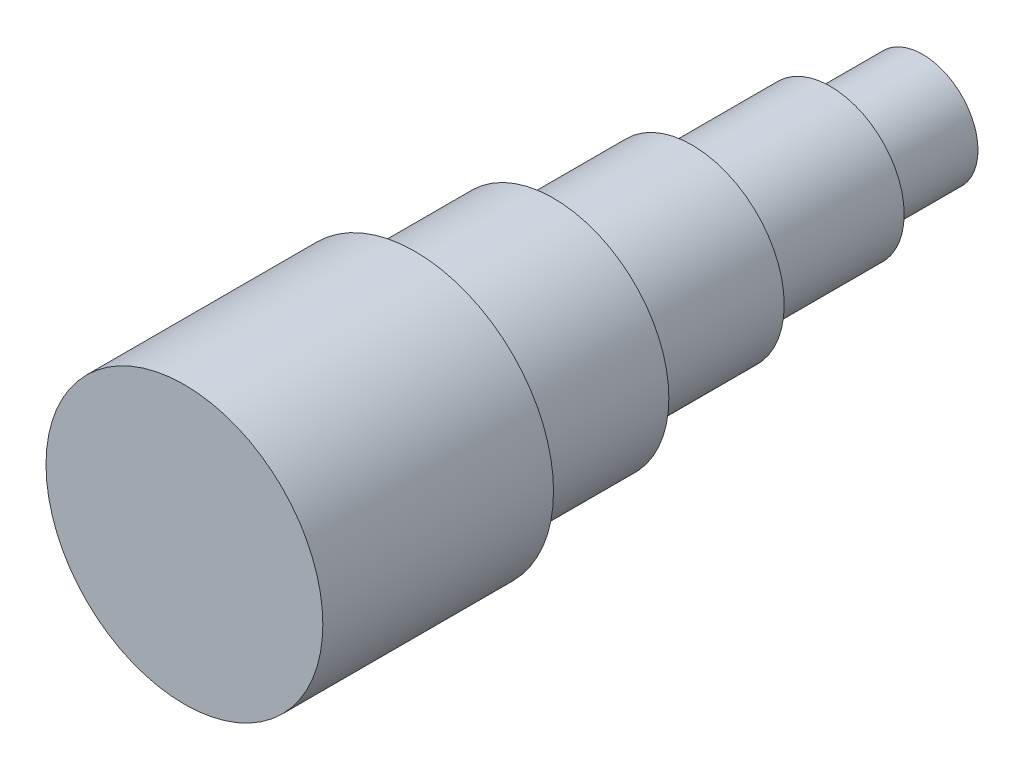
SolidWorks part; units mm, degrees
ref_plane "Front Plane" through (0, 0, 0) normal (0, 0, 1) x (1, 0, 0)
ref_plane "Top Plane" through (0, 0, 0) normal (0, 1, 0) x (1, 0, 0)
ref_plane "Right Plane" through (0, 0, 0) normal (1, 0, 0) x (0, 0, -1)
sketch "Sketch2" plane through (0, 0, 0) normal (1, 0, 0) x (0, 0, -1)
  line L0 (0, 0) -> (0, 15)
  line L1 (0, 15) -> (80, 15)
  line L2 (80, 15) -> (80, 0)
  line L3 (-1328.2767, 0) -> (65085.5576, 0) construction
  line L4 (2.5, 0) -> (2.5, 12.5)
  line L5 (2.5, 12.5) -> (77.5, 12.5)
  line L6 (71, 6) -> (80, 6)
  line L7 (2.5, 10) -> (75, 10)
  line L8 (80, 8) -> (73, 8)
  line L9 (2.5, 8) -> (73, 8)
  line L10 (75, 10) -> (80, 10)
  line L11 (2.5, 6) -> (71, 6)
  line L12 (77.5, 12.5) -> (80, 12.5)
  line L13 (25, 15) -> (25, 12.5)
  line L14 (25, 12.5) -> (40, 12.5)
  line L15 (40, 12.5) -> (40, 10)
  line L16 (40, 10) -> (55, 10)
  line L17 (55, 10) -> (55, 8)
  line L18 (55, 8) -> (70, 8)
  line L19 (70, 8) -> (70, 6)
  line L20 (80, 0) -> (0, 0)
  line L21 (71, 6) -> (71, 0) construction
  line L22 (73, 8) -> (73, 0) construction
  line L23 (75, 10) -> (75, 0) construction
  line L24 (77.5, 12.5) -> (77.5, 0) construction
  dimension "D1" = 80
  dimension "D2" = 15
  dimension "D7" = 10
  dimension "D8" = 25
  dimension "D9" = 40
  dimension "D10" = 55
  dimension "D3" = 2.5
  dimension "D4" = 2.5
  dimension "D5" = 2
  dimension "D6" = 2
revolve "VERSION3" add sketch "Sketch2" angle 360 about L3
